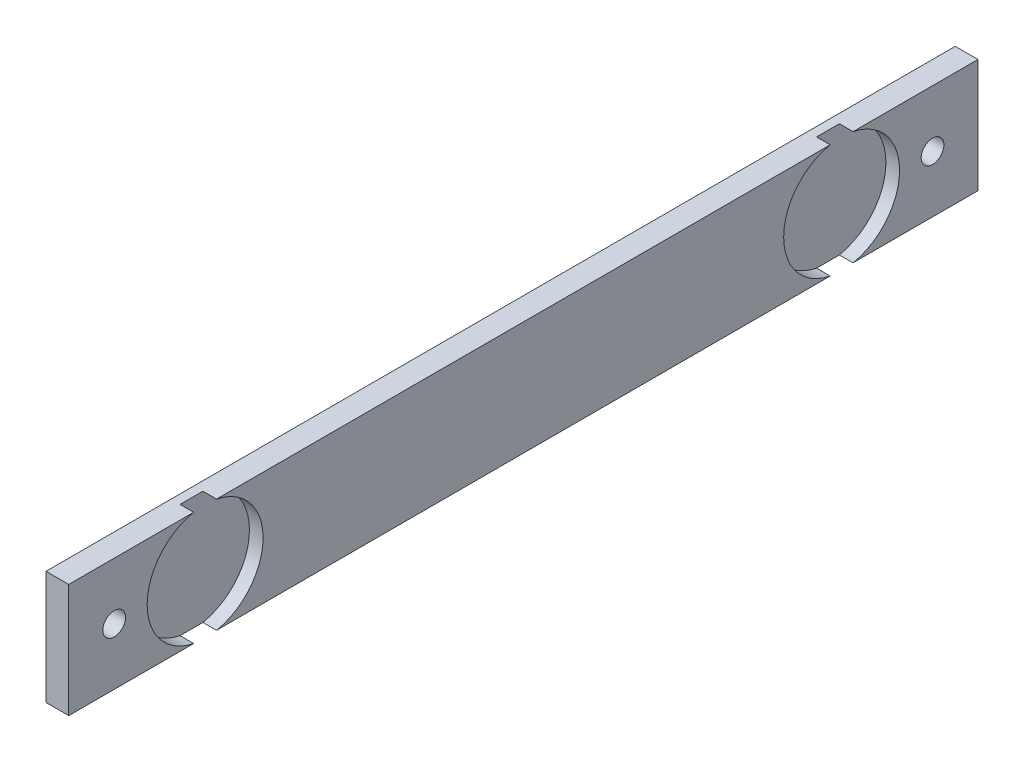
SolidWorks part; units mm, degrees
ref_plane "前视基准面" through (0, 0, 0) normal (0, 0, 1) x (1, 0, 0)
ref_plane "上视基准面" through (0, 0, 0) normal (0, 1, 0) x (1, 0, 0)
ref_plane "右视基准面" through (0, 0, 0) normal (1, 0, 0) x (0, 0, -1)
sketch "草图1" plane through (0, 0, 0) normal (1, 0, 0) x (0, 0, -1)
  line L1 (0, 0) -> (-80, 0)
  line L2 (0, 0) -> (0, 10)
  line L3 (0, 10) -> (-80, 10)
  line L4 (-80, 0) -> (-80, 10)
  dimension "D1" = 10
  dimension "D2" = 80
extrude "凸台-拉伸1" add sketch "草图1" along normal blind 2
sketch "草图2" plane through (2, 0, 0) normal (1, 0, 0) x (0, 0, -1)
  line L0 (-80, 10) -> (-80, 0) construction
  line L1 (0, 0) -> (0, 10) construction
  line L2 (0, 5) -> (-80, 5) construction
  circle A0 centre (-76, 5) radius 1
  circle A1 centre (-4, 5) radius 1
  point P10 (-4, 5)
  point P11 (-76, 5)
  dimension "D1" = 4
  dimension "D2" = 4
extrude "切除-拉伸1" cut sketch "草图2" against normal blind 2
sketch "草图5" plane through (2, 0, 0) normal (1, 0, 0) x (0, 0, -1)
  line L0 (-80, 10) -> (-80, 0) construction
  line L1 (0, 0) -> (0, 10) construction
  line L2 (0, 5) -> (-80, 5) construction
  circle A0 centre (-68, 5) radius 5.1
  circle A1 centre (-12, 5) radius 5.1
  point P10 (-14, 5.6591)
  point P11 (-14, 5)
  point P12 (0, 0)
  point P13 (-66, 5)
  dimension "D1" = 12
  dimension "D2" = 12
extrude "切除-拉伸2" cut sketch "草图5" against normal blind 1.2
